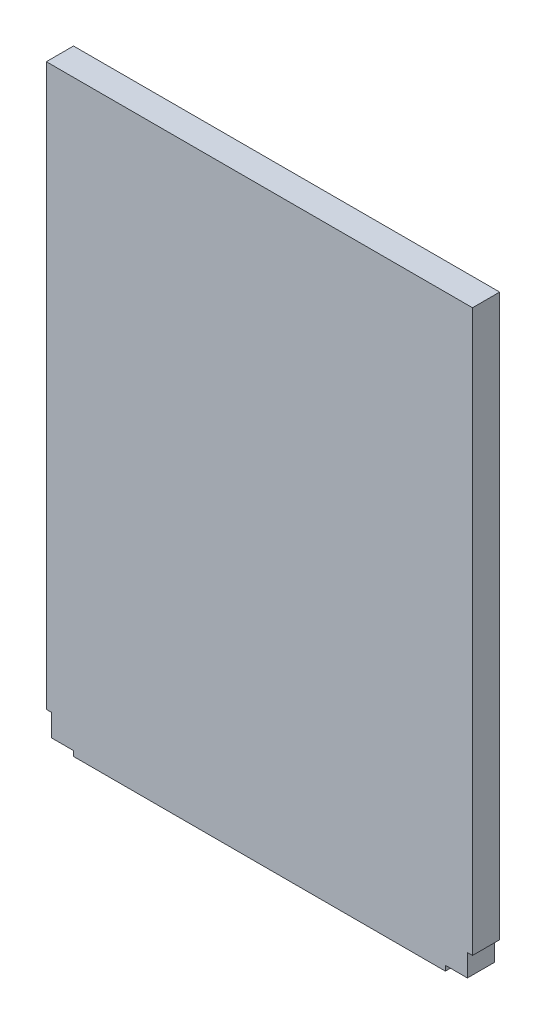
SolidWorks part; units mm, degrees
ref_plane "Alzado" through (0, 0, 0) normal (0, 0, 1) x (1, 0, 0)
ref_plane "Planta" through (0, 0, 0) normal (0, 1, 0) x (1, 0, 0)
ref_plane "Vista lateral" through (0, 0, 0) normal (1, 0, 0) x (0, 0, -1)
sketch "Croquis1" plane through (0, 0, 0) normal (0, 0, 1) x (1, 0, 0)
  line L1 (0, 0) -> (797.1, 0)
  line L2 (0, 0) -> (0, -1100)
  line L3 (0, -1100) -> (797.1, -1100)
  line L4 (797.1, 0) -> (797.1, -1100)
  dimension "D1" = 1100
  dimension "D2" = 797.1
extrude "Saliente-Extruir1" add sketch "Croquis1" along normal blind 50.8
sketch "Croquis2" plane through (0, 0, 50.8) normal (0, 0, 1) x (1, 0, 0)
  line L0 (0, -1049.2) -> (9.525, -1049.2)
  line L1 (0, 0) -> (0, -1100) construction
  line L2 (9.525, -1049.2) -> (9.525, -1090.475)
  line L3 (9.525, -1090.475) -> (50.8, -1090.475)
  line L4 (50.8, -1090.475) -> (50.8, -1100)
  line L5 (0, -1100) -> (797.1, -1100) construction
  line L6 (50.8, -1100) -> (0, -1100)
  line L7 (0, -1100) -> (0, -1049.2)
  line L8 (398.55, -1100) -> (398.55, -975.043) construction
  line L9 (797.1, -1100) -> (797.1, -1049.2)
  line L10 (746.3, -1100) -> (797.1, -1100)
  line L11 (746.3, -1090.475) -> (746.3, -1100)
  line L12 (787.575, -1090.475) -> (746.3, -1090.475)
  line L13 (787.575, -1049.2) -> (787.575, -1090.475)
  line L14 (797.1, -1049.2) -> (787.575, -1049.2)
  dimension "D1" = 50.8
  dimension "D2" = 50.8
  dimension "D3" = 9.525
  dimension "D4" = 9.525
extrude "Cortar-Extruir1" cut sketch "Croquis2" against normal blind 51
